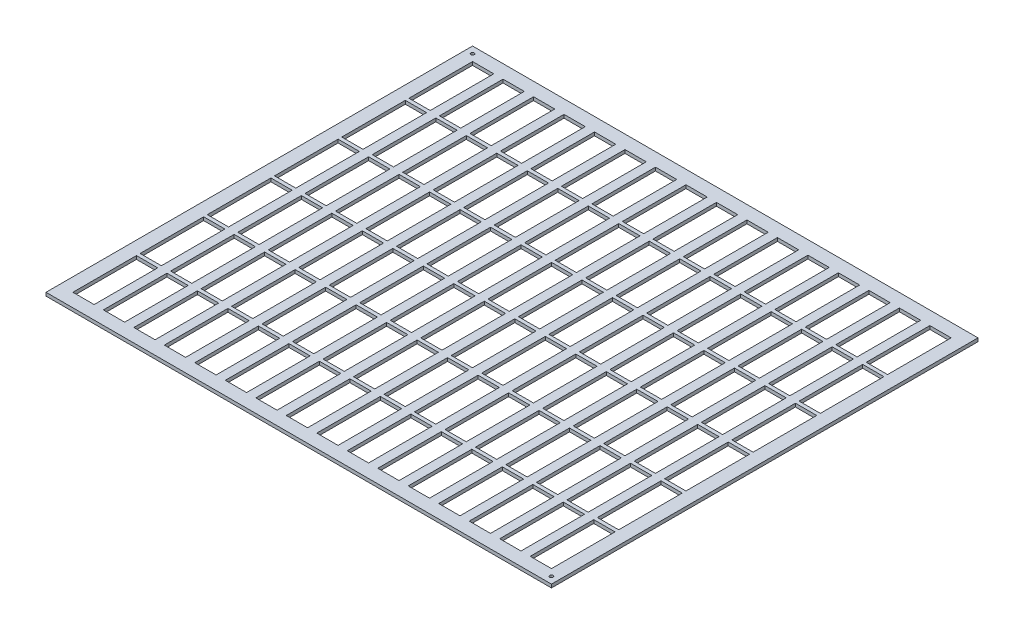
SolidWorks part; units mm, degrees
ref_plane "Front" through (0, 0, 0) normal (0, 0, 1) x (1, 0, 0)
ref_plane "Top" through (0, 0, 0) normal (0, 1, 0) x (1, 0, 0)
ref_plane "Right" through (0, 0, 0) normal (1, 0, 0) x (0, 0, -1)
sketch "Sketch1" plane through (0, 0, 0) normal (0, 1, 0) x (1, 0, 0)
  line L0 (0, -76.0537) -> (0, -227.7466) construction
  line L5 (-238.9187, -201.6125) -> (238.9188, -201.6125)
  line L6 (-238.9187, -201.6125) -> (-238.9187, 201.6125)
  line L7 (-238.9187, 201.6125) -> (238.9188, 201.6125)
  line L8 (238.9188, -201.6125) -> (238.9188, 201.6125)
  line L9 (-238.9187, -201.6125) -> (238.9188, 201.6125) construction
  line L10 (-238.9187, 201.6125) -> (238.9188, -201.6125) construction
  line L11 (55.3206, 0) -> (102.8784, 0) construction
  point P0 (0, 0)
  dimension "D1" = 477.8375
  dimension "D2" = 403.225
extrude "Boss-Extrude1" add sketch "Sketch1" along normal blind 3.175
sketch "Sketch2" plane through (0, 0, 0) normal (0, 1, 0) x (1, 0, 0)
  line L1 (-226.2187, 188.9125) -> (-206.1187, 188.9125)
  line L2 (-226.2187, 188.9125) -> (-226.2187, 128.8125)
  line L3 (-226.2187, 128.8125) -> (-206.1187, 128.8125)
  line L4 (-206.1187, 188.9125) -> (-206.1187, 128.8125)
  line L8 (206.1188, -128.8125) -> (226.2188, -128.8125) construction
  line L9 (206.1188, -128.8125) -> (206.1188, -188.9125) construction
  line L10 (206.1188, -188.9125) -> (226.2188, -188.9125) construction
  line L11 (226.2188, -128.8125) -> (226.2188, -188.9125) construction
  line L12 (-226.2187, -188.9125) -> (226.2188, -188.9125)
  line L13 (226.2188, -188.9125) -> (226.2188, 188.9125)
  line L14 (226.2188, 188.9125) -> (-226.2187, 188.9125)
  line L15 (-226.2187, 188.9125) -> (-226.2187, -188.9125)
  line L16 (-226.2187, -188.9125) -> (226.2188, -188.9125) construction
  line L17 (226.2188, -188.9125) -> (226.2188, 188.9125) construction
  line L18 (226.2188, 188.9125) -> (-226.2187, 188.9125) construction
  line L19 (-226.2187, 188.9125) -> (-226.2187, -188.9125) construction
  line L20 (216.1688, -128.8125) -> (216.1688, -188.9125) construction
  line L21 (206.1188, -158.8625) -> (226.2188, -158.8625) construction
  dimension "D1" = 60.1
  dimension "D2" = 20.1
  dimension "D3" = 12.7
extrude "Cut-Extrude1" cut sketch "Sketch2" along normal through all
pattern_linear "LPattern2" count 16 spacing 28.8225 along (1, 0, 0) count 6 spacing 63.545 along (0, 0, 1) of "Cut-Extrude1"
sketch "Sketch4" plane through (0, 0, 0) normal (0, 1, 0) x (1, 0, 0)
  line L0 (-238.9187, -201.6125) -> (238.9188, -201.6125) construction
  line L1 (238.9188, -201.6125) -> (238.9188, 201.6125) construction
  line L2 (238.9188, 201.6125) -> (-238.9187, 201.6125) construction
  line L3 (-238.9187, 201.6125) -> (-238.9187, -201.6125) construction
  circle A0 centre (-232.5687, 195.2625) radius 1.5875
  circle A1 centre (232.5688, -195.2625) radius 1.5875
  dimension "D3" = 3.175
  dimension "D6" = 3.175
  dimension "D1" = 6.35
  dimension "D2" = 6.35
  dimension "D4" = 6.35
  dimension "D5" = 6.35
extrude "Cut-Extrude2" cut sketch "Sketch4" along normal through all
sketch "Sketch5" plane through (0, 0, 0) normal (0, 1, 0) x (1, 0, 0)
  line L0 (238.9188, -201.6125) -> (238.9188, 201.6125) construction
  line L9 (-238.9187, -201.6125) -> (238.9188, -201.6125) construction
  line L10 (-238.9187, 201.6125) -> (-238.9187, -201.6125) construction
  line L11 (238.9188, 201.6125) -> (-238.9187, 201.6125) construction
  line L12 (238.9188, -201.6125) -> (238.9188, 201.6125)
  line L13 (-238.9187, -201.6125) -> (238.9188, -201.6125)
  line L14 (-238.9187, 201.6125) -> (-238.9187, -201.6125)
  line L15 (238.9188, 201.6125) -> (-238.9187, 201.6125)
  line L16 (-206.1187, 128.8125) -> (-206.1187, 188.9125) construction
  line L17 (-206.1187, 188.9125) -> (-226.2187, 188.9125) construction
  line L18 (-226.2187, 128.8125) -> (-206.1187, 128.8125) construction
  line L19 (-226.2187, 188.9125) -> (-226.2187, 128.8125) construction
  line L20 (-226.2187, 128.8125) -> (-206.1187, 128.8125)
  line L21 (-206.1187, 188.9125) -> (-226.2187, 188.9125)
  line L22 (-206.1187, 128.8125) -> (-206.1187, 188.9125)
  line L23 (-226.2187, 188.9125) -> (-226.2187, 128.8125)
  line L24 (-180.7187, 188.9125) -> (-200.8187, 188.9125)
  line L25 (-226.2187, 188.9125) -> (-206.1187, 188.9125)
  line L26 (-226.2187, 188.9125) -> (-226.2187, 128.8125)
  line L27 (-226.2187, 128.8125) -> (-206.1187, 128.8125)
  line L28 (-206.1187, 188.9125) -> (-206.1187, 128.8125)
  line L29 (-200.8187, 188.9125) -> (-200.8187, 128.8125)
  line L30 (-200.8187, 128.8125) -> (-180.7187, 128.8125)
  line L31 (-180.7187, 128.8125) -> (-180.7187, 188.9125)
  line L32 (-155.3187, 188.9125) -> (-175.4187, 188.9125)
  line L33 (-175.4187, 188.9125) -> (-175.4187, 128.8125)
  line L34 (-175.4187, 128.8125) -> (-155.3187, 128.8125)
  line L35 (-155.3187, 128.8125) -> (-155.3187, 188.9125)
  line L36 (-129.9187, 188.9125) -> (-150.0187, 188.9125)
  line L37 (-150.0187, 188.9125) -> (-150.0187, 128.8125)
  line L38 (-150.0187, 128.8125) -> (-129.9187, 128.8125)
  line L39 (-129.9187, 128.8125) -> (-129.9187, 188.9125)
  line L40 (-104.5187, 188.9125) -> (-124.6187, 188.9125)
  line L41 (-124.6187, 188.9125) -> (-124.6187, 128.8125)
  line L42 (-124.6187, 128.8125) -> (-104.5187, 128.8125)
  line L43 (-104.5187, 128.8125) -> (-104.5187, 188.9125)
  line L44 (-79.1187, 188.9125) -> (-99.2187, 188.9125)
  line L45 (-99.2187, 188.9125) -> (-99.2187, 128.8125)
  line L46 (-99.2187, 128.8125) -> (-79.1187, 128.8125)
  line L47 (-79.1187, 128.8125) -> (-79.1187, 188.9125)
  line L48 (-53.7187, 188.9125) -> (-73.8187, 188.9125)
  line L49 (-73.8187, 188.9125) -> (-73.8187, 128.8125)
  line L50 (-73.8187, 128.8125) -> (-53.7187, 128.8125)
  line L51 (-53.7187, 128.8125) -> (-53.7187, 188.9125)
  line L52 (-28.3187, 188.9125) -> (-48.4187, 188.9125)
  line L53 (-48.4187, 188.9125) -> (-48.4187, 128.8125)
  line L54 (-48.4187, 128.8125) -> (-28.3187, 128.8125)
  line L55 (-28.3187, 128.8125) -> (-28.3187, 188.9125)
  line L56 (-2.9187, 188.9125) -> (-23.0187, 188.9125)
  line L57 (-23.0187, 188.9125) -> (-23.0187, 128.8125)
  line L58 (-23.0187, 128.8125) -> (-2.9187, 128.8125)
  line L59 (-2.9187, 128.8125) -> (-2.9187, 188.9125)
  line L60 (22.4813, 188.9125) -> (2.3813, 188.9125)
  line L61 (2.3813, 188.9125) -> (2.3813, 128.8125)
  line L62 (2.3813, 128.8125) -> (22.4813, 128.8125)
  line L63 (22.4813, 128.8125) -> (22.4813, 188.9125)
  line L64 (47.8813, 188.9125) -> (27.7813, 188.9125)
  line L65 (27.7813, 188.9125) -> (27.7813, 128.8125)
  line L66 (27.7813, 128.8125) -> (47.8813, 128.8125)
  line L67 (47.8813, 128.8125) -> (47.8813, 188.9125)
  line L68 (73.2813, 188.9125) -> (53.1813, 188.9125)
  line L69 (53.1813, 188.9125) -> (53.1813, 128.8125)
  line L70 (53.1813, 128.8125) -> (73.2813, 128.8125)
  line L71 (73.2813, 128.8125) -> (73.2813, 188.9125)
  line L72 (98.6813, 188.9125) -> (78.5813, 188.9125)
  line L73 (78.5813, 188.9125) -> (78.5813, 128.8125)
  line L74 (78.5813, 128.8125) -> (98.6813, 128.8125)
  line L75 (98.6813, 128.8125) -> (98.6813, 188.9125)
  line L76 (124.0813, 188.9125) -> (103.9813, 188.9125)
  line L77 (103.9813, 188.9125) -> (103.9813, 128.8125)
  line L78 (103.9813, 128.8125) -> (124.0813, 128.8125)
  line L79 (124.0813, 128.8125) -> (124.0813, 188.9125)
  line L80 (149.4813, 188.9125) -> (129.3813, 188.9125)
  line L81 (129.3813, 188.9125) -> (129.3813, 128.8125)
  line L82 (129.3813, 128.8125) -> (149.4813, 128.8125)
  line L83 (149.4813, 128.8125) -> (149.4813, 188.9125)
  line L84 (174.8813, 188.9125) -> (154.7813, 188.9125)
  line L85 (154.7813, 188.9125) -> (154.7813, 128.8125)
  line L86 (154.7813, 128.8125) -> (174.8813, 128.8125)
  line L87 (174.8813, 128.8125) -> (174.8813, 188.9125)
  line L88 (-180.7187, 125.4125) -> (-200.8187, 125.4125)
  line L89 (-200.8187, 125.4125) -> (-200.8187, 65.3125)
  line L90 (-200.8187, 65.3125) -> (-180.7187, 65.3125)
  line L91 (-180.7187, 65.3125) -> (-180.7187, 125.4125)
  line L92 (-155.3187, 125.4125) -> (-175.4187, 125.4125)
  line L93 (-175.4187, 125.4125) -> (-175.4187, 65.3125)
  line L94 (-175.4187, 65.3125) -> (-155.3187, 65.3125)
  line L95 (-155.3187, 65.3125) -> (-155.3187, 125.4125)
  line L96 (-129.9187, 125.4125) -> (-150.0187, 125.4125)
  line L97 (-150.0187, 125.4125) -> (-150.0187, 65.3125)
  line L98 (-150.0187, 65.3125) -> (-129.9187, 65.3125)
  line L99 (-129.9187, 65.3125) -> (-129.9187, 125.4125)
  line L100 (-104.5187, 125.4125) -> (-124.6187, 125.4125)
  line L101 (-124.6187, 125.4125) -> (-124.6187, 65.3125)
  line L102 (-124.6187, 65.3125) -> (-104.5187, 65.3125)
  line L103 (-104.5187, 65.3125) -> (-104.5187, 125.4125)
  line L104 (-79.1187, 125.4125) -> (-99.2187, 125.4125)
  line L105 (-99.2187, 125.4125) -> (-99.2187, 65.3125)
  line L106 (-99.2187, 65.3125) -> (-79.1187, 65.3125)
  line L107 (-79.1187, 65.3125) -> (-79.1187, 125.4125)
  line L108 (-53.7187, 125.4125) -> (-73.8187, 125.4125)
  line L109 (-73.8187, 125.4125) -> (-73.8187, 65.3125)
  line L110 (-73.8187, 65.3125) -> (-53.7187, 65.3125)
  line L111 (-53.7187, 65.3125) -> (-53.7187, 125.4125)
  line L112 (-28.3187, 125.4125) -> (-48.4187, 125.4125)
  line L113 (-48.4187, 125.4125) -> (-48.4187, 65.3125)
  line L114 (-48.4187, 65.3125) -> (-28.3187, 65.3125)
  line L115 (-28.3187, 65.3125) -> (-28.3187, 125.4125)
  line L116 (-2.9187, 125.4125) -> (-23.0187, 125.4125)
  line L117 (-23.0187, 125.4125) -> (-23.0187, 65.3125)
  line L118 (-23.0187, 65.3125) -> (-2.9187, 65.3125)
  line L119 (-2.9187, 65.3125) -> (-2.9187, 125.4125)
  line L120 (22.4813, 125.4125) -> (2.3813, 125.4125)
  line L121 (2.3813, 125.4125) -> (2.3813, 65.3125)
  line L122 (2.3813, 65.3125) -> (22.4813, 65.3125)
  line L123 (22.4813, 65.3125) -> (22.4813, 125.4125)
  line L124 (47.8813, 125.4125) -> (27.7813, 125.4125)
  line L125 (27.7813, 125.4125) -> (27.7813, 65.3125)
  line L126 (27.7813, 65.3125) -> (47.8813, 65.3125)
  line L127 (47.8813, 65.3125) -> (47.8813, 125.4125)
  line L128 (73.2813, 125.4125) -> (53.1813, 125.4125)
  line L129 (53.1813, 125.4125) -> (53.1813, 65.3125)
  line L130 (53.1813, 65.3125) -> (73.2813, 65.3125)
  line L131 (73.2813, 65.3125) -> (73.2813, 125.4125)
  line L132 (98.6813, 125.4125) -> (78.5813, 125.4125)
  line L133 (78.5813, 125.4125) -> (78.5813, 65.3125)
  line L134 (78.5813, 65.3125) -> (98.6813, 65.3125)
  line L135 (98.6813, 65.3125) -> (98.6813, 125.4125)
  line L136 (124.0813, 125.4125) -> (103.9813, 125.4125)
  line L137 (103.9813, 125.4125) -> (103.9813, 65.3125)
  line L138 (103.9813, 65.3125) -> (124.0813, 65.3125)
  line L139 (124.0813, 65.3125) -> (124.0813, 125.4125)
  line L140 (149.4813, 125.4125) -> (129.3813, 125.4125)
  line L141 (129.3813, 125.4125) -> (129.3813, 65.3125)
  line L142 (129.3813, 65.3125) -> (149.4813, 65.3125)
  line L143 (149.4813, 65.3125) -> (149.4813, 125.4125)
  line L144 (174.8813, 125.4125) -> (154.7813, 125.4125)
  line L145 (154.7813, 125.4125) -> (154.7813, 65.3125)
  line L146 (154.7813, 65.3125) -> (174.8813, 65.3125)
  line L147 (174.8813, 65.3125) -> (174.8813, 125.4125)
  line L148 (-180.7187, 61.9125) -> (-200.8187, 61.9125)
  line L149 (-200.8187, 61.9125) -> (-200.8187, 1.8125)
  line L150 (-200.8187, 1.8125) -> (-180.7187, 1.8125)
  line L151 (-180.7187, 1.8125) -> (-180.7187, 61.9125)
  line L152 (-155.3187, 61.9125) -> (-175.4187, 61.9125)
  line L153 (-175.4187, 61.9125) -> (-175.4187, 1.8125)
  line L154 (-175.4187, 1.8125) -> (-155.3187, 1.8125)
  line L155 (-155.3187, 1.8125) -> (-155.3187, 61.9125)
  line L156 (-129.9187, 61.9125) -> (-150.0187, 61.9125)
  line L157 (-150.0187, 61.9125) -> (-150.0187, 1.8125)
  line L158 (-150.0187, 1.8125) -> (-129.9187, 1.8125)
  line L159 (-129.9187, 1.8125) -> (-129.9187, 61.9125)
  line L160 (-104.5187, 61.9125) -> (-124.6187, 61.9125)
  line L161 (-124.6187, 61.9125) -> (-124.6187, 1.8125)
  line L162 (-124.6187, 1.8125) -> (-104.5187, 1.8125)
  line L163 (-104.5187, 1.8125) -> (-104.5187, 61.9125)
  line L164 (-79.1187, 61.9125) -> (-99.2187, 61.9125)
  line L165 (-99.2187, 61.9125) -> (-99.2187, 1.8125)
  line L166 (-99.2187, 1.8125) -> (-79.1187, 1.8125)
  line L167 (-79.1187, 1.8125) -> (-79.1187, 61.9125)
  line L168 (-53.7187, 61.9125) -> (-73.8187, 61.9125)
  line L169 (-73.8187, 61.9125) -> (-73.8187, 1.8125)
  line L170 (-73.8187, 1.8125) -> (-53.7187, 1.8125)
  line L171 (-53.7187, 1.8125) -> (-53.7187, 61.9125)
  line L172 (-28.3187, 61.9125) -> (-48.4187, 61.9125)
  line L173 (-48.4187, 61.9125) -> (-48.4187, 1.8125)
  line L174 (-48.4187, 1.8125) -> (-28.3187, 1.8125)
  line L175 (-28.3187, 1.8125) -> (-28.3187, 61.9125)
  line L176 (-2.9187, 61.9125) -> (-23.0187, 61.9125)
  line L177 (-23.0187, 61.9125) -> (-23.0187, 1.8125)
  line L178 (-23.0187, 1.8125) -> (-2.9187, 1.8125)
  line L179 (-2.9187, 1.8125) -> (-2.9187, 61.9125)
  line L180 (22.4813, 61.9125) -> (2.3813, 61.9125)
  line L181 (2.3813, 61.9125) -> (2.3813, 1.8125)
  line L182 (2.3813, 1.8125) -> (22.4813, 1.8125)
  line L183 (22.4813, 1.8125) -> (22.4813, 61.9125)
  line L184 (47.8813, 61.9125) -> (27.7813, 61.9125)
  line L185 (27.7813, 61.9125) -> (27.7813, 1.8125)
  line L186 (27.7813, 1.8125) -> (47.8813, 1.8125)
  line L187 (47.8813, 1.8125) -> (47.8813, 61.9125)
  line L188 (73.2813, 61.9125) -> (53.1813, 61.9125)
  line L189 (53.1813, 61.9125) -> (53.1813, 1.8125)
  line L190 (53.1813, 1.8125) -> (73.2813, 1.8125)
  line L191 (73.2813, 1.8125) -> (73.2813, 61.9125)
  line L192 (98.6813, 61.9125) -> (78.5813, 61.9125)
  line L193 (78.5813, 61.9125) -> (78.5813, 1.8125)
  line L194 (78.5813, 1.8125) -> (98.6813, 1.8125)
  line L195 (98.6813, 1.8125) -> (98.6813, 61.9125)
  line L196 (124.0813, 61.9125) -> (103.9813, 61.9125)
  line L197 (103.9813, 61.9125) -> (103.9813, 1.8125)
  line L198 (103.9813, 1.8125) -> (124.0813, 1.8125)
  line L199 (124.0813, 1.8125) -> (124.0813, 61.9125)
  line L200 (149.4813, 61.9125) -> (129.3813, 61.9125)
  line L201 (129.3813, 61.9125) -> (129.3813, 1.8125)
  line L202 (129.3813, 1.8125) -> (149.4813, 1.8125)
  line L203 (149.4813, 1.8125) -> (149.4813, 61.9125)
  line L204 (174.8813, 61.9125) -> (154.7813, 61.9125)
  line L205 (154.7813, 61.9125) -> (154.7813, 1.8125)
  line L206 (154.7813, 1.8125) -> (174.8813, 1.8125)
  line L207 (174.8813, 1.8125) -> (174.8813, 61.9125)
  line L208 (-180.7187, -1.5875) -> (-200.8187, -1.5875)
  line L209 (-200.8187, -1.5875) -> (-200.8187, -61.6875)
  line L210 (-200.8187, -61.6875) -> (-180.7187, -61.6875)
  line L211 (-180.7187, -61.6875) -> (-180.7187, -1.5875)
  line L212 (-155.3187, -1.5875) -> (-175.4187, -1.5875)
  line L213 (-175.4187, -1.5875) -> (-175.4187, -61.6875)
  line L214 (-175.4187, -61.6875) -> (-155.3187, -61.6875)
  line L215 (-155.3187, -61.6875) -> (-155.3187, -1.5875)
  line L216 (-129.9187, -1.5875) -> (-150.0187, -1.5875)
  line L217 (-150.0187, -1.5875) -> (-150.0187, -61.6875)
  line L218 (-150.0187, -61.6875) -> (-129.9187, -61.6875)
  line L219 (-129.9187, -61.6875) -> (-129.9187, -1.5875)
  line L220 (-104.5187, -1.5875) -> (-124.6187, -1.5875)
  line L221 (-124.6187, -1.5875) -> (-124.6187, -61.6875)
  line L222 (-124.6187, -61.6875) -> (-104.5187, -61.6875)
  line L223 (-104.5187, -61.6875) -> (-104.5187, -1.5875)
  line L224 (-79.1187, -1.5875) -> (-99.2187, -1.5875)
  line L225 (-99.2187, -1.5875) -> (-99.2187, -61.6875)
  line L226 (-99.2187, -61.6875) -> (-79.1187, -61.6875)
  line L227 (-79.1187, -61.6875) -> (-79.1187, -1.5875)
  line L228 (-53.7187, -1.5875) -> (-73.8187, -1.5875)
  line L229 (-73.8187, -1.5875) -> (-73.8187, -61.6875)
  line L230 (-73.8187, -61.6875) -> (-53.7187, -61.6875)
  line L231 (-53.7187, -61.6875) -> (-53.7187, -1.5875)
  line L232 (-28.3187, -1.5875) -> (-48.4187, -1.5875)
  line L233 (-48.4187, -1.5875) -> (-48.4187, -61.6875)
  line L234 (-48.4187, -61.6875) -> (-28.3187, -61.6875)
  line L235 (-28.3187, -61.6875) -> (-28.3187, -1.5875)
  line L236 (-2.9187, -1.5875) -> (-23.0187, -1.5875)
  line L237 (-23.0187, -1.5875) -> (-23.0187, -61.6875)
  line L238 (-23.0187, -61.6875) -> (-2.9187, -61.6875)
  line L239 (-2.9187, -61.6875) -> (-2.9187, -1.5875)
  line L240 (22.4813, -1.5875) -> (2.3813, -1.5875)
  line L241 (2.3813, -1.5875) -> (2.3813, -61.6875)
  line L242 (2.3813, -61.6875) -> (22.4813, -61.6875)
  line L243 (22.4813, -61.6875) -> (22.4813, -1.5875)
  line L244 (47.8813, -1.5875) -> (27.7813, -1.5875)
  line L245 (27.7813, -1.5875) -> (27.7813, -61.6875)
  line L246 (27.7813, -61.6875) -> (47.8813, -61.6875)
  line L247 (47.8813, -61.6875) -> (47.8813, -1.5875)
  line L248 (73.2813, -1.5875) -> (53.1813, -1.5875)
  line L249 (53.1813, -1.5875) -> (53.1813, -61.6875)
  line L250 (53.1813, -61.6875) -> (73.2813, -61.6875)
  line L251 (73.2813, -61.6875) -> (73.2813, -1.5875)
  line L252 (98.6813, -1.5875) -> (78.5813, -1.5875)
  line L253 (78.5813, -1.5875) -> (78.5813, -61.6875)
  line L254 (78.5813, -61.6875) -> (98.6813, -61.6875)
  line L255 (98.6813, -61.6875) -> (98.6813, -1.5875)
  line L256 (124.0813, -1.5875) -> (103.9813, -1.5875)
  line L257 (103.9813, -1.5875) -> (103.9813, -61.6875)
  line L258 (103.9813, -61.6875) -> (124.0813, -61.6875)
  line L259 (124.0813, -61.6875) -> (124.0813, -1.5875)
  line L260 (149.4813, -1.5875) -> (129.3813, -1.5875)
  line L261 (129.3813, -1.5875) -> (129.3813, -61.6875)
  line L262 (129.3813, -61.6875) -> (149.4813, -61.6875)
  line L263 (149.4813, -61.6875) -> (149.4813, -1.5875)
  line L264 (174.8813, -1.5875) -> (154.7813, -1.5875)
  line L265 (154.7813, -1.5875) -> (154.7813, -61.6875)
  line L266 (154.7813, -61.6875) -> (174.8813, -61.6875)
  line L267 (174.8813, -61.6875) -> (174.8813, -1.5875)
  line L268 (-180.7187, -65.0875) -> (-200.8187, -65.0875)
  line L269 (-200.8187, -65.0875) -> (-200.8187, -125.1875)
  line L270 (-200.8187, -125.1875) -> (-180.7187, -125.1875)
  line L271 (-180.7187, -125.1875) -> (-180.7187, -65.0875)
  line L272 (-155.3187, -65.0875) -> (-175.4187, -65.0875)
  line L273 (-175.4187, -65.0875) -> (-175.4187, -125.1875)
  line L274 (-175.4187, -125.1875) -> (-155.3187, -125.1875)
  line L275 (-155.3187, -125.1875) -> (-155.3187, -65.0875)
  line L276 (-129.9187, -65.0875) -> (-150.0187, -65.0875)
  line L277 (-150.0187, -65.0875) -> (-150.0187, -125.1875)
  line L278 (-150.0187, -125.1875) -> (-129.9187, -125.1875)
  line L279 (-129.9187, -125.1875) -> (-129.9187, -65.0875)
  line L280 (-104.5187, -65.0875) -> (-124.6187, -65.0875)
  line L281 (-124.6187, -65.0875) -> (-124.6187, -125.1875)
  line L282 (-124.6187, -125.1875) -> (-104.5187, -125.1875)
  line L283 (-104.5187, -125.1875) -> (-104.5187, -65.0875)
  line L284 (-79.1187, -65.0875) -> (-99.2187, -65.0875)
  line L285 (-99.2187, -65.0875) -> (-99.2187, -125.1875)
  line L286 (-99.2187, -125.1875) -> (-79.1187, -125.1875)
  line L287 (-79.1187, -125.1875) -> (-79.1187, -65.0875)
  line L288 (-53.7187, -65.0875) -> (-73.8187, -65.0875)
  line L289 (-73.8187, -65.0875) -> (-73.8187, -125.1875)
  line L290 (-73.8187, -125.1875) -> (-53.7187, -125.1875)
  line L291 (-53.7187, -125.1875) -> (-53.7187, -65.0875)
  line L292 (-28.3187, -65.0875) -> (-48.4187, -65.0875)
  line L293 (-48.4187, -65.0875) -> (-48.4187, -125.1875)
  line L294 (-48.4187, -125.1875) -> (-28.3187, -125.1875)
  line L295 (-28.3187, -125.1875) -> (-28.3187, -65.0875)
  line L296 (-2.9187, -65.0875) -> (-23.0187, -65.0875)
  line L297 (-23.0187, -65.0875) -> (-23.0187, -125.1875)
  line L298 (-23.0187, -125.1875) -> (-2.9187, -125.1875)
  line L299 (-2.9187, -125.1875) -> (-2.9187, -65.0875)
  line L300 (22.4813, -65.0875) -> (2.3813, -65.0875)
  line L301 (2.3813, -65.0875) -> (2.3813, -125.1875)
  line L302 (2.3813, -125.1875) -> (22.4813, -125.1875)
  line L303 (22.4813, -125.1875) -> (22.4813, -65.0875)
  line L304 (47.8813, -65.0875) -> (27.7813, -65.0875)
  line L305 (27.7813, -65.0875) -> (27.7813, -125.1875)
  line L306 (27.7813, -125.1875) -> (47.8813, -125.1875)
  line L307 (47.8813, -125.1875) -> (47.8813, -65.0875)
  line L308 (73.2813, -65.0875) -> (53.1813, -65.0875)
  line L309 (53.1813, -65.0875) -> (53.1813, -125.1875)
  line L310 (53.1813, -125.1875) -> (73.2813, -125.1875)
  line L311 (73.2813, -125.1875) -> (73.2813, -65.0875)
  line L312 (98.6813, -65.0875) -> (78.5813, -65.0875)
  line L313 (78.5813, -65.0875) -> (78.5813, -125.1875)
  line L314 (78.5813, -125.1875) -> (98.6813, -125.1875)
  line L315 (98.6813, -125.1875) -> (98.6813, -65.0875)
  line L316 (124.0813, -65.0875) -> (103.9813, -65.0875)
  line L317 (103.9813, -65.0875) -> (103.9813, -125.1875)
  line L318 (103.9813, -125.1875) -> (124.0813, -125.1875)
  line L319 (124.0813, -125.1875) -> (124.0813, -65.0875)
  line L320 (149.4813, -65.0875) -> (129.3813, -65.0875)
  line L321 (129.3813, -65.0875) -> (129.3813, -125.1875)
  line L322 (129.3813, -125.1875) -> (149.4813, -125.1875)
  line L323 (149.4813, -125.1875) -> (149.4813, -65.0875)
  line L324 (174.8813, -65.0875) -> (154.7813, -65.0875)
  line L325 (154.7813, -65.0875) -> (154.7813, -125.1875)
  line L326 (154.7813, -125.1875) -> (174.8813, -125.1875)
  line L327 (174.8813, -125.1875) -> (174.8813, -65.0875)
  line L328 (-180.7187, -128.5875) -> (-200.8187, -128.5875)
  line L329 (-200.8187, -128.5875) -> (-200.8187, -188.6875)
  line L330 (-200.8187, -188.6875) -> (-180.7187, -188.6875)
  line L331 (-180.7187, -188.6875) -> (-180.7187, -128.5875)
  line L332 (-155.3187, -128.5875) -> (-175.4187, -128.5875)
  line L333 (-175.4187, -128.5875) -> (-175.4187, -188.6875)
  line L334 (-175.4187, -188.6875) -> (-155.3187, -188.6875)
  line L335 (-155.3187, -188.6875) -> (-155.3187, -128.5875)
  line L336 (-129.9187, -128.5875) -> (-150.0187, -128.5875)
  line L337 (-150.0187, -128.5875) -> (-150.0187, -188.6875)
  line L338 (-150.0187, -188.6875) -> (-129.9187, -188.6875)
  line L339 (-129.9187, -188.6875) -> (-129.9187, -128.5875)
  line L340 (-104.5187, -128.5875) -> (-124.6187, -128.5875)
  line L341 (-124.6187, -128.5875) -> (-124.6187, -188.6875)
  line L342 (-124.6187, -188.6875) -> (-104.5187, -188.6875)
  line L343 (-104.5187, -188.6875) -> (-104.5187, -128.5875)
  line L344 (-79.1187, -128.5875) -> (-99.2187, -128.5875)
  line L345 (-99.2187, -128.5875) -> (-99.2187, -188.6875)
  line L346 (-99.2187, -188.6875) -> (-79.1187, -188.6875)
  line L347 (-79.1187, -188.6875) -> (-79.1187, -128.5875)
  line L348 (-53.7187, -128.5875) -> (-73.8187, -128.5875)
  line L349 (-73.8187, -128.5875) -> (-73.8187, -188.6875)
  line L350 (-73.8187, -188.6875) -> (-53.7187, -188.6875)
  line L351 (-53.7187, -188.6875) -> (-53.7187, -128.5875)
  line L352 (-28.3187, -128.5875) -> (-48.4187, -128.5875)
  line L353 (-48.4187, -128.5875) -> (-48.4187, -188.6875)
  line L354 (-48.4187, -188.6875) -> (-28.3187, -188.6875)
  line L355 (-28.3187, -188.6875) -> (-28.3187, -128.5875)
  line L356 (-2.9187, -128.5875) -> (-23.0187, -128.5875)
  line L357 (-23.0187, -128.5875) -> (-23.0187, -188.6875)
  line L358 (-23.0187, -188.6875) -> (-2.9187, -188.6875)
  line L359 (-2.9187, -188.6875) -> (-2.9187, -128.5875)
  line L360 (22.4813, -128.5875) -> (2.3813, -128.5875)
  line L361 (2.3813, -128.5875) -> (2.3813, -188.6875)
  line L362 (2.3813, -188.6875) -> (22.4813, -188.6875)
  line L363 (22.4813, -188.6875) -> (22.4813, -128.5875)
  line L364 (47.8813, -128.5875) -> (27.7813, -128.5875)
  line L365 (27.7813, -128.5875) -> (27.7813, -188.6875)
  line L366 (27.7813, -188.6875) -> (47.8813, -188.6875)
  line L367 (47.8813, -188.6875) -> (47.8813, -128.5875)
  line L368 (73.2813, -128.5875) -> (53.1813, -128.5875)
  line L369 (53.1813, -128.5875) -> (53.1813, -188.6875)
  line L370 (53.1813, -188.6875) -> (73.2813, -188.6875)
  line L371 (73.2813, -188.6875) -> (73.2813, -128.5875)
  line L372 (98.6813, -128.5875) -> (78.5813, -128.5875)
  line L373 (78.5813, -128.5875) -> (78.5813, -188.6875)
  line L374 (78.5813, -188.6875) -> (98.6813, -188.6875)
  line L375 (98.6813, -188.6875) -> (98.6813, -128.5875)
  line L376 (124.0813, -128.5875) -> (103.9813, -128.5875)
  line L377 (103.9813, -128.5875) -> (103.9813, -188.6875)
  line L378 (103.9813, -188.6875) -> (124.0813, -188.6875)
  line L379 (124.0813, -188.6875) -> (124.0813, -128.5875)
  line L380 (149.4813, -128.5875) -> (129.3813, -128.5875)
  line L381 (129.3813, -128.5875) -> (129.3813, -188.6875)
  line L382 (129.3813, -188.6875) -> (149.4813, -188.6875)
  line L383 (149.4813, -188.6875) -> (149.4813, -128.5875)
  line L384 (174.8813, -128.5875) -> (154.7813, -128.5875)
  line L385 (154.7813, -128.5875) -> (154.7813, -188.6875)
  line L386 (154.7813, -188.6875) -> (174.8813, -188.6875)
  line L387 (174.8813, -188.6875) -> (174.8813, -128.5875)
  line L388 (-206.1187, 125.4125) -> (-226.2187, 125.4125)
  line L389 (-226.2187, 125.4125) -> (-226.2187, 65.3125)
  line L390 (-226.2187, 65.3125) -> (-206.1187, 65.3125)
  line L391 (-206.1187, 65.3125) -> (-206.1187, 125.4125)
  line L392 (-206.1187, 61.9125) -> (-226.2187, 61.9125)
  line L393 (-226.2187, 61.9125) -> (-226.2187, 1.8125)
  line L394 (-226.2187, 1.8125) -> (-206.1187, 1.8125)
  line L395 (-206.1187, 1.8125) -> (-206.1187, 61.9125)
  line L396 (-206.1187, -1.5875) -> (-226.2187, -1.5875)
  line L397 (-226.2187, -1.5875) -> (-226.2187, -61.6875)
  line L398 (-226.2187, -61.6875) -> (-206.1187, -61.6875)
  line L399 (-206.1187, -61.6875) -> (-206.1187, -1.5875)
  line L400 (-206.1187, -65.0875) -> (-226.2187, -65.0875)
  line L401 (-226.2187, -65.0875) -> (-226.2187, -125.1875)
  line L402 (-226.2187, -125.1875) -> (-206.1187, -125.1875)
  line L403 (-206.1187, -125.1875) -> (-206.1187, -65.0875)
  line L404 (-206.1187, -128.5875) -> (-226.2187, -128.5875)
  line L405 (-226.2187, -128.5875) -> (-226.2187, -188.6875)
  line L406 (-226.2187, -188.6875) -> (-206.1187, -188.6875)
  line L407 (-206.1187, -188.6875) -> (-206.1187, -128.5875)
  line L408 (-206.1187, 188.9125) -> (-180.7187, 188.9125) construction
  line L409 (-206.1187, 188.9125) -> (-206.1187, 125.4125) construction
  circle A0 centre (-232.5687, 195.2625) radius 1.5875 construction
  circle A1 centre (232.5688, -195.2625) radius 1.5875 construction
  circle A2 centre (-232.5687, 195.2625) radius 1.5875
  circle A3 centre (232.5688, -195.2625) radius 1.5875
  dimension "D3" = 25.4
  dimension "D4" = 63.5
  dimension "D1" = 16
  dimension "D2" = 6
